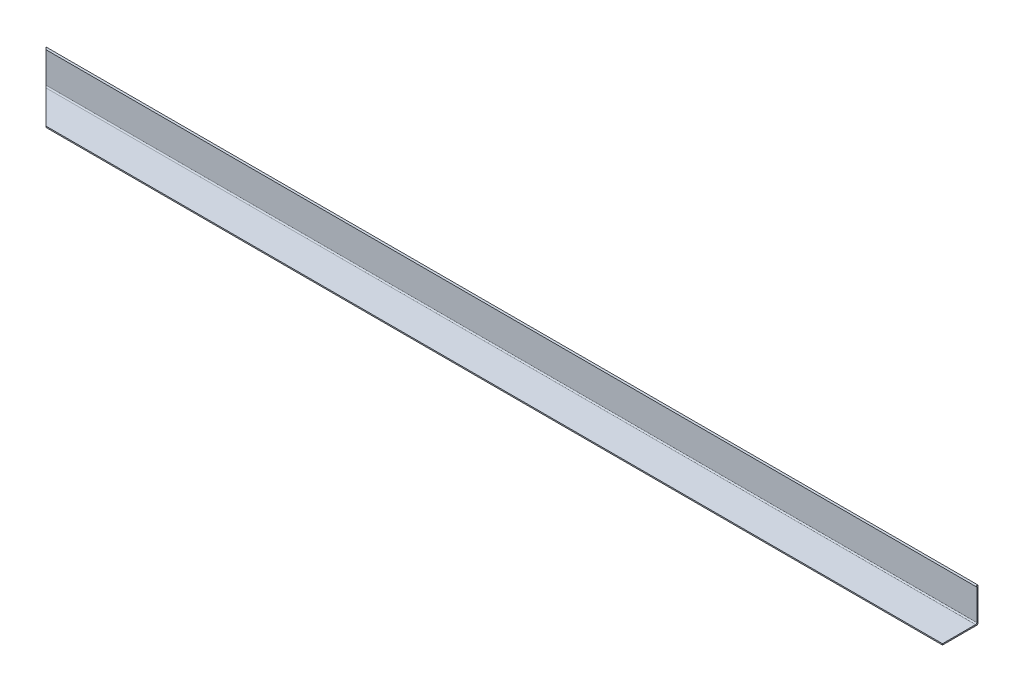
SolidWorks part; units mm, degrees
ref_plane "Front Plane" through (0, 0, 0) normal (0, 0, 1) x (1, 0, 0)
ref_plane "Top Plane" through (0, 0, 0) normal (0, 1, 0) x (1, 0, 0)
ref_plane "Right Plane" through (0, 0, 0) normal (1, 0, 0) x (0, 0, -1)
sketch "Sketch1" plane through (0, 0, 0) normal (1, 0, 0) x (0, 0, -1)
  line L0 (0, 0) -> (85, 0)
  line L1 (85, 0) -> (85, 82)
  line L2 (85, 82) -> (47, 82)
  line L3 (47, 82) -> (47, 112)
  line L4 (0, -3) -> (88, -3)
  line L5 (88, -3) -> (88, 85)
  line L6 (88, 85) -> (50, 85)
  line L7 (50, 85) -> (50, 112)
  line L8 (47, 112) -> (50, 112)
  line L9 (0, 0) -> (0, -3)
  point P11 (48.5, 112)
  dimension "D1" = 3
  dimension "D2" = 27
  dimension "D3" = 38
  dimension "D4" = 88
  dimension "D5" = 88
extrude "Boss-Extrude1" add sketch "Sketch1" along normal blind 2310
fillet "Fillet1" radius 3 6 edges at (1155, -3, -88) (1155, 85, -88) (1155, 85, -50) (1155, 82, -85) (1155, 0, -85) (1155, 82, -47)
sketch "Sketch2" plane through (0, -3, 0) normal (0, -1, 0) x (1, 0, 0)
  line L0 (0, -88) -> (88, 0)
  line L1 (2310, 0) -> (0, 0) construction
  line L2 (88, 0) -> (0, 0)
  line L3 (0, 0) -> (0, -88)
  dimension "D1" = 45
extrude "Cut-Extrude1" cut sketch "Sketch2" against normal blind 85
sketch "Sketch3" plane through (0, 0, -47) normal (0, 0, 1) x (1, 0, 0)
  line L0 (0, 112) -> (2310, 112)
  line L1 (2310, 112) -> (0, 112) construction
  line L2 (2310, 112) -> (2310, 82)
  line L3 (6, 82) -> (2310, 82) construction
  line L4 (2310, 82) -> (0, 82)
  line L5 (0, 82) -> (0, 112)
  dimension "D1" = 2310
extrude "Cut-Extrude2" cut sketch "Sketch3" against normal blind 41
equation "\"D1@Boss-Extrude1\"= \"indoorHeight\" + \"indoorHeight_para\" + 80 + \"rearLightHeight_para\""
equation "\"CarBeamWidth\"=700.0"
equation "\"WheelWidth\"=650.0"
equation "\"Wheel_FrontBoxDistance\"=1390.0"
equation "\"boxLength\"=5100.0"
equation "\"boxWidth\"=1930.0"
equation "\"MetalSheet_3mm_length\"=5030.0"
equation "\"MetalSheet_3mm_width\"=1923.0"
equation "\"MetalSheet_3mm_FloorCut_L_length\"=1764.0"
equation "\"MetalSheet_3mm_FloorCut_L_disdance\"=1665.0"
equation "\"MetalSheet_3mm_FloorCut_R_length\"=1764.0"
equation "\"MetalSheet_3mm_FloorCut_R_disdance\"=1665.0"
equation "\"indoorHeight\"=1940.0"
equation "\"indoorHeight_para\"=25.0"
equation "\"rearLightHeight_para\"=265.0"
equation "\"haveDoor_R\"=1"
equation "\"side_door_bottom_R_3mm_length\"=1934.0"
equation "\"side_door_bottom_R_3mm_toFrontDistance\"=1583.0"
equation "\"1Bar_Side_RF_3mm_length\"=1493.0"
equation "\"1Bar_Side_RB_3mm_length\"=1493.0"
equation "\"DoorSeparator_RF_3mm_withHinge_toFrontDistance\"=1673.0"
equation "\"DoorSeparator_RF_3mm_withHinge_exist\"=1"
equation "\"DoorSeparator_RB_3mm_withHinge_toFrontDistance\"=3427.0"
equation "\"DoorSeparator_RB_3mm_withHinge_exist\"=1"
equation "\"Door_R1_L_open_Single_toFrontDistance\"=2547.5"
equation "\"Door_R1_L_open_Single_exist\"=1"
equation "\"door_base_long7_R1_L_open_Single_height\"=1890.0"
equation "\"door_base_short7_R1_L_open_Single_height\"=1890.0"
equation "\"door_base_short7_R1_L_open_Single_width\"=864"
equation "\"Door_R1_R_open_Single_toFrontDistance\"=3422.0"
equation "\"Door_R1_R_open_Single_exist\"=1"
equation "\"door_base_long7_R1_R_open_Single_height\"=1890.0"
equation "\"door_base_short7_R1_R_open_Single_height\"=1890.0"
equation "\"door_base_short7_R1_R_open_Single_width\"=864"
equation "\"x\"=66.0"
equation "\"door_base_double_BL_height\"=1890.0"
equation "\"door_base_short7_BL_Single_height\"=1890.0"
equation "\"door_base_short7_BL_Single_width\"=864"
equation "\"door_base_long7_BR_Single_height\"=1890.0"
equation "\"door_base_short7_BR_Single_height\"=1890.0"
equation "\"door_base_short7_BR_Single_width\"=864"
equation "\"da\"=62.0"
equation "\"SquareTube_length\"=1923.0"
equation "\"channelSteel_length\"=5030.0"
equation "\"SquareTube_inFront_AvgDistance\"=285.0"
equation "\"SquareTube_inFront_TotalCount\"=5"
equation "\"SquareTube_inFront1_cutDepth50_R\"=0.5"
equation "\"SquareTube_inFront1_cutDepth50_L\"=0.5"
equation "\"SquareTube_inFront2_cutDepth50_R\"=0.5"
equation "\"SquareTube_inFront2_cutDepth50_L\"=0.5"
equation "\"SquareTube_inFront3_cutDepth50_R\"=0.5"
equation "\"SquareTube_inFront3_cutDepth50_L\"=0.5"
equation "\"SquareTube_inFront4_cutDepth50_R\"=0.5"
equation "\"SquareTube_inFront4_cutDepth50_L\"=0.5"
equation "\"SquareTube_inFront5_cutDepth50_R\"=50"
equation "\"SquareTube_inFront5_cutDepth50_L\"=50"
equation "\"SquareTube_inFront6_cutDepth50_R\"=50"
equation "\"SquareTube_inFront6_cutDepth50_L\"=50"
equation "\"SquareTube_inFront7_cutDepth50_R\"=50"
equation "\"SquareTube_inFront7_cutDepth50_L\"=50"
equation "\"SquareTube_inFront8_cutDepth50_R\"=50"
equation "\"SquareTube_inFront8_cutDepth50_L\"=50"
equation "\"SquareTube_inFront9_cutDepth50_R\"=50"
equation "\"SquareTube_inFront9_cutDepth50_L\"=50"
equation "\"SquareTube_inFront10_cutDepth50_R\"=50"
equation "\"SquareTube_inFront10_cutDepth50_L\"=50"
equation "\"SquareTube_inFront11_cutDepth50_R\"=50"
equation "\"SquareTube_inFront11_cutDepth50_L\"=50"
equation "\"SquareTube_inFront12_cutDepth50_R\"=50"
equation "\"SquareTube_inFront12_cutDepth50_L\"=50"
equation "\"SquareTube_inFront13_cutDepth50_R\"=50"
equation "\"SquareTube_inFront13_cutDepth50_L\"=50"
equation "\"SquareTube_inFront14_cutDepth50_R\"=50"
equation "\"SquareTube_inFront14_cutDepth50_L\"=50"
equation "\"SquareTube_inBack_AvgDistance\"=333.125"
equation "\"SquareTube_inBack_TotalCount\"=9"
equation "\"SquareTube_inBack1_cutDepth50_R\"=50"
equation "\"SquareTube_inBack1_cutDepth50_L\"=50"
equation "\"SquareTube_inBack2_cutDepth50_R\"=50"
equation "\"SquareTube_inBack2_cutDepth50_L\"=50"
equation "\"SquareTube_inBack3_cutDepth50_R\"=50"
equation "\"SquareTube_inBack3_cutDepth50_L\"=50"
equation "\"SquareTube_inBack4_cutDepth50_R\"=50"
equation "\"SquareTube_inBack4_cutDepth50_L\"=50"
equation "\"SquareTube_inBack5_cutDepth50_R\"=50"
equation "\"SquareTube_inBack5_cutDepth50_L\"=50"
equation "\"SquareTube_inBack6_cutDepth50_R\"=0.5"
equation "\"SquareTube_inBack6_cutDepth50_L\"=0.5"
equation "\"SquareTube_inBack7_cutDepth50_R\"=0.5"
equation "\"SquareTube_inBack7_cutDepth50_L\"=0.5"
equation "\"SquareTube_inBack8_cutDepth50_R\"=0.5"
equation "\"SquareTube_inBack8_cutDepth50_L\"=0.5"
equation "\"doorColumnBar_A_FR_3mm_length_Cut\"=2310.0"
equation "\"D1@Sketch3\"=\"doorColumnBar_A_FR_3mm_length_Cut\""
equation "\"A\"=0.0"
